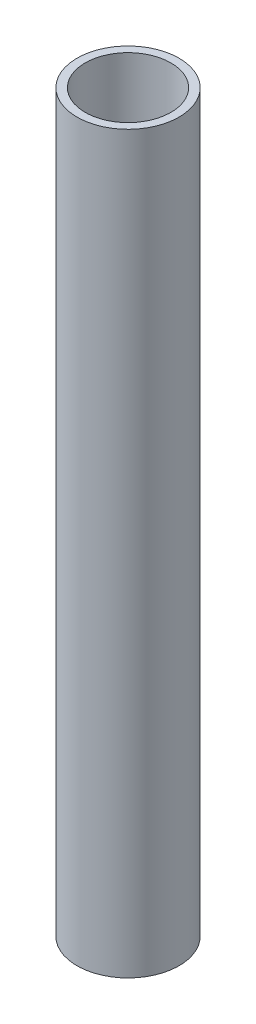
SolidWorks part; units mm, degrees
material "PVC 0.007 塑化"
ref_plane "前视基准面" through (0, 0, 0) normal (0, 0, 1) x (1, 0, 0)
ref_plane "上视基准面" through (0, 0, 0) normal (0, 1, 0) x (1, 0, 0)
ref_plane "右视基准面" through (0, 0, 0) normal (1, 0, 0) x (0, 0, -1)
sketch "草图1" plane through (0, 0, 0) normal (0, 1, 0) x (1, 0, 0)
  circle A0 centre (0, 0) radius 12.5
  circle A1 centre (0, 0) radius 10.5
  dimension "D1" = 21
  dimension "D2" = 25
extrude "凸台-拉伸1" add sketch "草图1" along normal blind 180 contours A0 | A1
